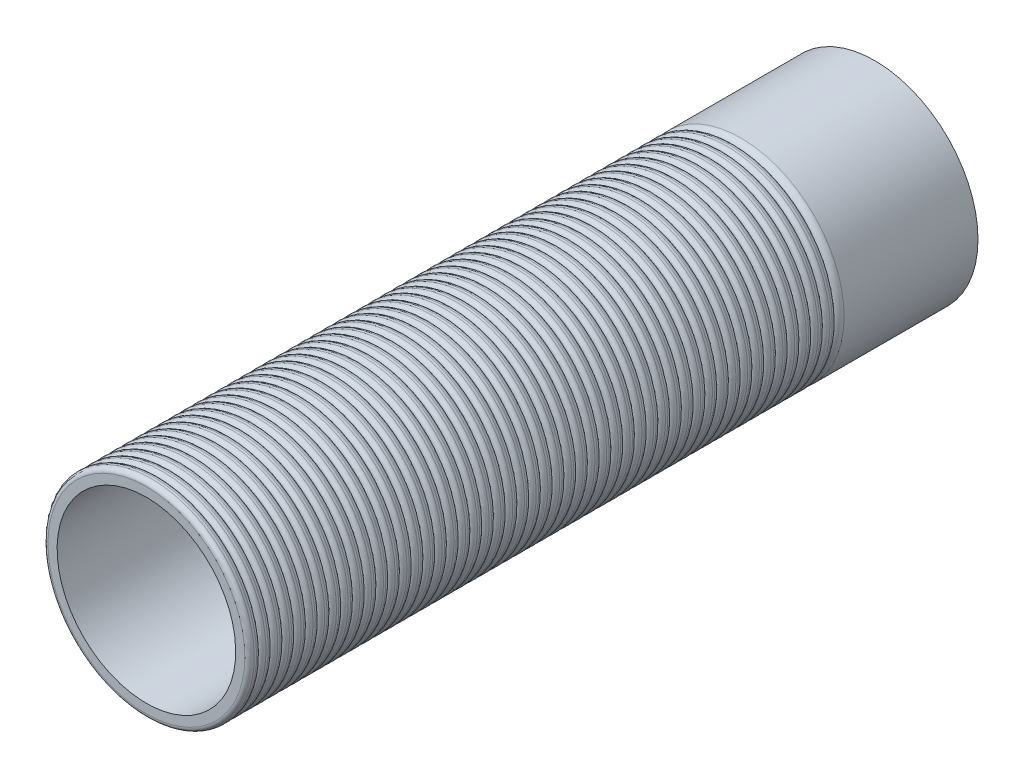
SolidWorks part; units mm, degrees
material "PVC Rigid"
ref_plane "Front Plane" through (0, 0, 0) normal (0, 0, 1) x (1, 0, 0)
ref_plane "Top Plane" through (0, 0, 0) normal (0, 1, 0) x (1, 0, 0)
ref_plane "Right Plane" through (0, 0, 0) normal (1, 0, 0) x (0, 0, -1)
sketch "Sketch1" plane through (0, 0, 0) normal (0, 0, 1) x (1, 0, 0)
  circle A0 centre (0, 0) radius 38
  circle A1 centre (0, 0) radius 43.9
  dimension "D1" = 76
  dimension "D2" = 87.8
extrude "Boss-Extrude1" add sketch "Sketch1" along normal blind 60
fillet "Fillet1" radius 3 1 edges at (43.9, 0, 60)
sketch "Sketch2" plane through (0, 0, 0) normal (1, 0, 0) x (0, 0, -1)
  line L0 (-60, 38) -> (-65, 38)
  line L1 (-65, 38) -> (-65, 41.9)
  line L2 (-63, 43.9) -> (-62, 43.9)
  line L3 (-60, 41.9) -> (-60, 38)
  line L4 (0, 43.9) -> (-57, 43.9) construction
  line L5 (0, 0) -> (-60, 0) construction
  line L8 (-60, 40.9) -> (-60, -40.9) construction
  arc A0 (-60, 41.9) -> (-62, 43.9) centre (-62, 41.9) ccw
  arc A1 (-63, 43.9) -> (-65, 41.9) centre (-63, 41.9) ccw
  dimension "D2" = 2
  dimension "D1" = 5
revolve "Revolve1" add sketch "Sketch2" angle 360 about L5
pattern_linear "LPattern1" count 50 spacing 5 along (0, 0, 1) of "Revolve1"
